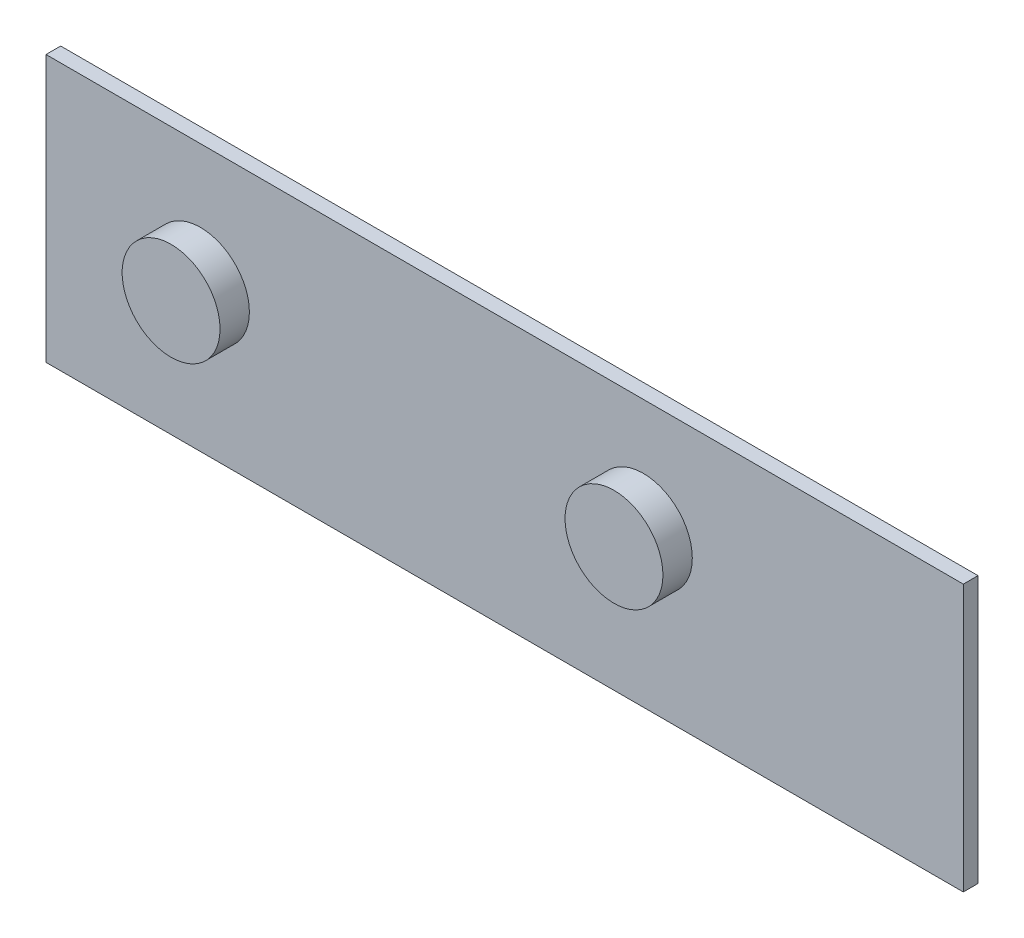
SolidWorks part; units mm, degrees
ref_plane "Front Plane" through (0, 0, 0) normal (0, 0, 1) x (1, 0, 0)
ref_plane "Top Plane" through (0, 0, 0) normal (0, 1, 0) x (1, 0, 0)
ref_plane "Right Plane" through (0, 0, 0) normal (1, 0, 0) x (0, 0, -1)
sketch "Sketch1" plane through (0, 0, 0) normal (0, 0, 1) x (1, 0, 0)
  line L1 (-69.2098, 54.4835) -> (118.2283, 54.4835)
  line L2 (-69.2098, 54.4835) -> (-69.2098, 0)
  line L3 (-69.2098, 0) -> (118.2283, 0)
  line L4 (118.2283, 54.4835) -> (118.2283, 0)
  point P4 (-26.0693, 27.2417)
  point P5 (63.9307, 27.2417)
  dimension "D1" = 90
extrude "Boss-Extrude1" add sketch "Sketch1" along normal blind 3
sketch "Sketch2" plane through (0, 0, 3) normal (0, 0, 1) x (1, 0, 0)
  circle A0 centre (-37.6501, 29.675) radius 10
  circle A1 centre (52.8499, 31.3926) radius 10
  dimension "D1" = 90.5
extrude "Boss-Extrude2" add sketch "Sketch2" along normal blind 6
